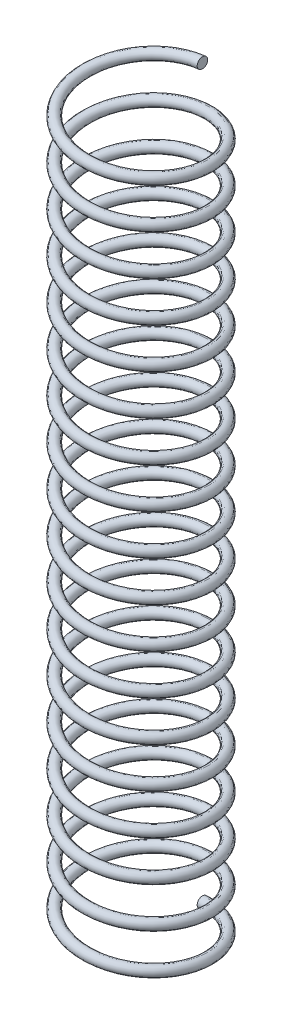
SolidWorks part; units mm, degrees
material "1060 Alloy"
ref_plane "Front Plane" through (0, 0, 0) normal (0, 0, 1) x (1, 0, 0)
ref_plane "Top Plane" through (0, 0, 0) normal (0, 1, 0) x (1, 0, 0)
ref_plane "Right Plane" through (0, 0, 0) normal (1, 0, 0) x (0, 0, -1)
sketch "Sketch1" plane through (0, 0, 0) normal (0, 1, 0) x (1, 0, 0)
  circle A0 centre (0, 0) radius 7
  dimension "D1" = 14
curve "Helix/Spiral1" pitch 4.6 height 82.8 turns 18
sketch "Sketch3" plane through (0, 0, 0) normal (1, 0, 0) x (0, 0, -1)
  circle A0 centre (7, 0) radius 0.6
  dimension "D1" = 1.2
  dimension "D2" = 7
sweep "Sweep1" add profiles "Sketch3" path "Helix/Spiral1"
